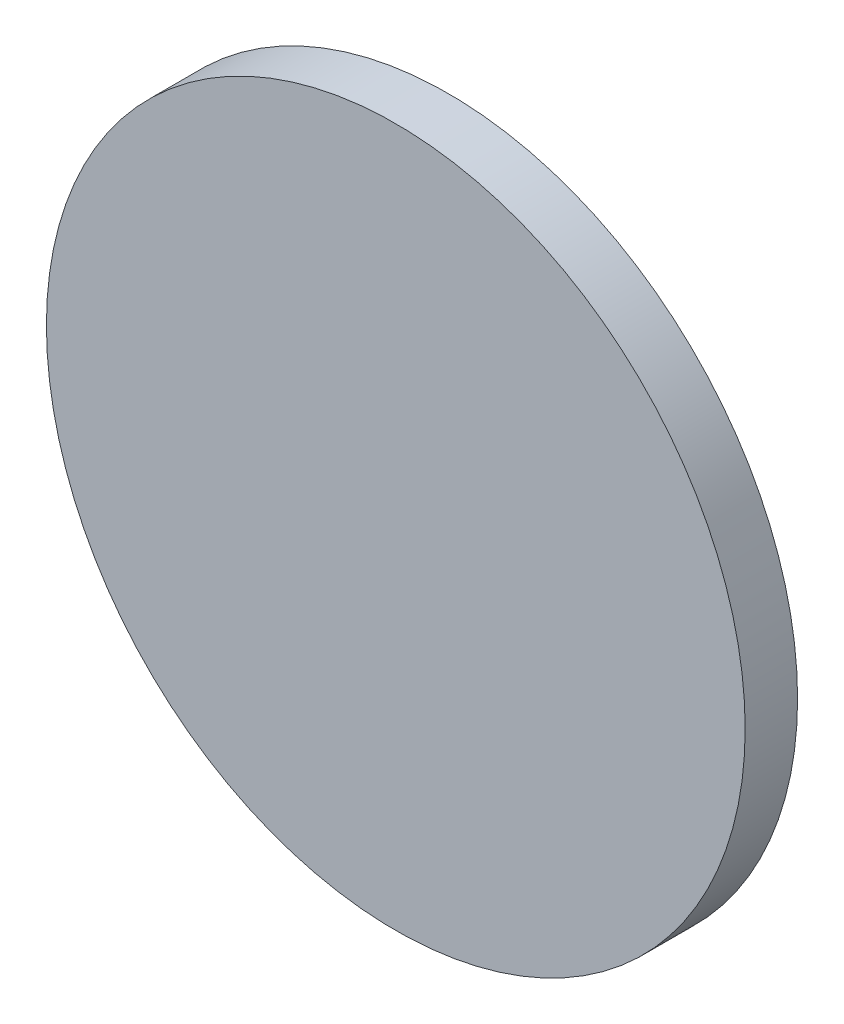
SolidWorks part; units mm, degrees
ref_plane "Plan de face" through (0, 0, 0) normal (0, 0, 1) x (1, 0, 0)
ref_plane "Plan de dessus" through (0, 0, 0) normal (0, 1, 0) x (1, 0, 0)
ref_plane "Plan de droite" through (0, 0, 0) normal (1, 0, 0) x (0, 0, -1)
sketch "Esquisse1" plane through (0, 0, 0) normal (0, 0, 1) x (1, 0, 0)
  circle A0 centre (0, 0) radius 20
  dimension "D1" = 40
extrude "Boss.-Extru.1" add sketch "Esquisse1" along normal blind 3 contours A0
